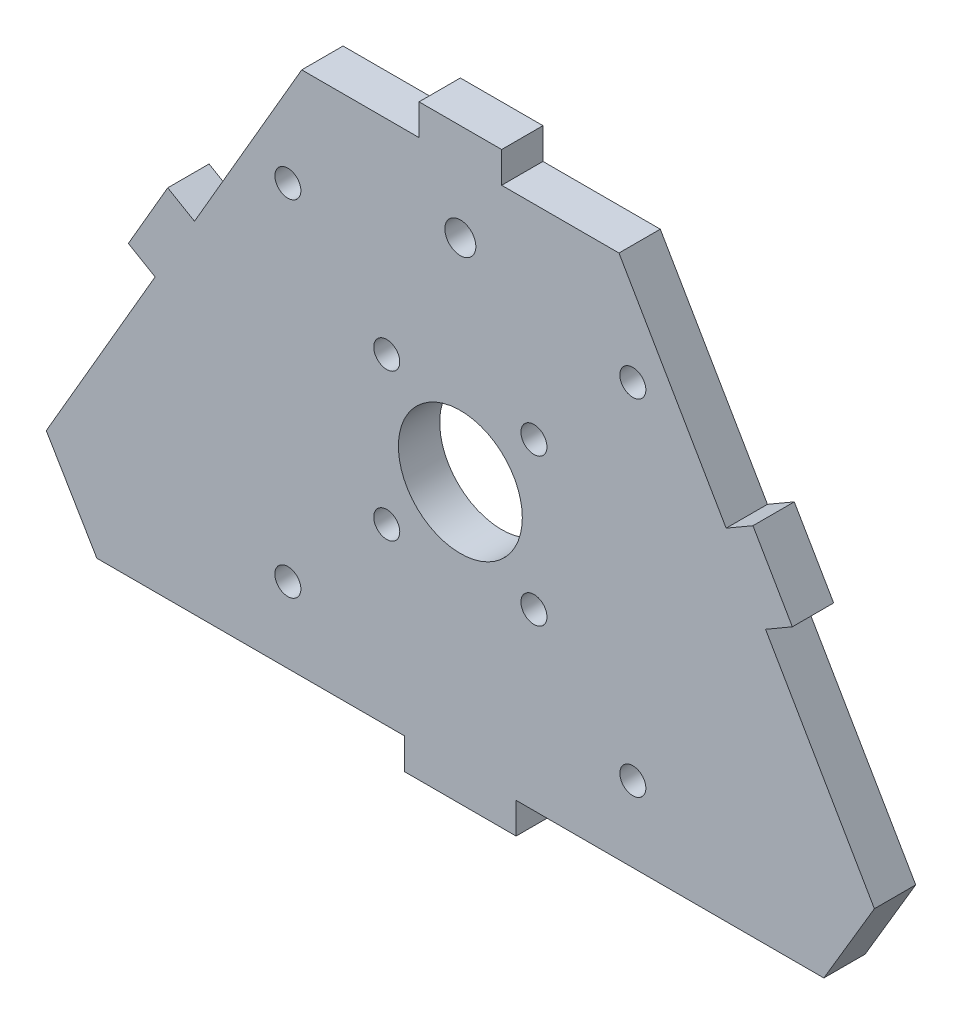
SolidWorks part; units mm, degrees
material "Teak"
ref_plane "Front Plane" through (0, 0, 0) normal (0, 0, 1) x (1, 0, 0)
ref_plane "Top Plane" through (0, 0, 0) normal (0, 1, 0) x (1, 0, 0)
ref_plane "Right Plane" through (0, 0, 0) normal (1, 0, 0) x (0, 0, -1)
sketch "Sketch2" plane through (0, 0, 0) normal (0, 0, 1) x (1, 0, 0)
  line L0 (0, 0) -> (0, -48.7674) construction
  line L1 (0, 0) -> (-45.5415, 0) construction
  line L2 (0, 0) -> (0, 80.772) construction
  line L3 (24.384, 80.772) -> (-24.384, 80.772)
  line L4 (-24.384, 80.772) -> (-63.6522, 13.1092)
  line L7 (-55.88, 0) -> (55.88, 0)
  line L8 (-63.6522, 13.1092) -> (-55.88, 0)
  line L9 (63.6522, 13.1092) -> (55.88, 0)
  line L10 (24.384, 80.772) -> (63.6522, 13.1092)
  dimension "D1" = 80.772
  dimension "D2" = 55.88
  dimension "D3" = 24.384
  dimension "D4" = 15.24
  dimension "D5" = 78.232
extrude "Boss-Extrude1" add sketch "Sketch2" along normal blind 6.35
sketch "Sketch3" plane through (0, 0, 6.35) normal (0, 0, 1) x (1, 0, 0)
  line L0 (0, 80.772) -> (0, 0) construction
  line L2 (0, 38.1) -> (49.1487, 38.1) construction
  line L7 (-11.3137, 49.4137) -> (11.3137, 49.4137) construction
  line L8 (-11.3137, 49.4137) -> (-11.3137, 26.7863) construction
  line L13 (-11.3137, 26.7863) -> (11.3137, 26.7863) construction
  line L14 (11.3137, 49.4137) -> (11.3137, 26.7863) construction
  line L15 (-11.3137, 49.4137) -> (11.3137, 26.7863) construction
  line L16 (-11.3137, 26.7863) -> (11.3137, 49.4137) construction
  line L17 (-26.5165, 64.6165) -> (26.5165, 64.6165) construction
  line L18 (-26.5165, 64.6165) -> (-26.5165, 11.5835) construction
  line L19 (-26.5165, 11.5835) -> (26.5165, 11.5835) construction
  line L20 (26.5165, 64.6165) -> (26.5165, 11.5835) construction
  line L21 (-26.5165, 64.6165) -> (26.5165, 11.5835) construction
  line L22 (-26.5165, 11.5835) -> (26.5165, 64.6165) construction
  line L23 (24.384, 80.772) -> (-24.384, 80.772) construction
  line L24 (-55.88, 0) -> (55.88, 0) construction
  line L25 (63.6522, 13.1092) -> (24.384, 80.772) construction
  circle A10 centre (0, 38.1) radius 9.525
  circle A11 centre (-11.3137, 49.4137) radius 2
  circle A12 centre (-11.3137, 26.7863) radius 2
  circle A13 centre (11.3137, 26.7863) radius 2
  circle A14 centre (11.3137, 49.4137) radius 2
  circle A15 centre (26.5165, 64.6165) radius 2
  circle A16 centre (-26.5165, 64.6165) radius 2
  circle A17 centre (-26.5165, 11.5835) radius 2
  circle A18 centre (26.5165, 11.5835) radius 2
  circle A19 centre (0, 70.612) radius 2.3812
  point P22 (0, 0)
  dimension "D1" = 32
  dimension "D2" = 75
  dimension "D5" = 38.1
  dimension "D7" = 10.16
  dimension "D3" = 19.05
  dimension "D4" = 4
  dimension "D6" = 4.7625
extrude "Cut-Extrude1" cut sketch "Sketch3" against normal blind 6.35
sketch "Sketch4" plane through (0, 0, 0) normal (0, -1, 0) x (1, 0, 0)
  line L0 (0, 6.35) -> (0, 0) construction
  line L1 (-55.88, 6.35) -> (55.88, 6.35) construction
  line L2 (-55.88, 0) -> (55.88, 0) construction
  line L3 (-8.5725, 6.35) -> (8.5725, 6.35)
  line L4 (-8.5725, 6.35) -> (-8.5725, 0)
  line L5 (-8.5725, 0) -> (8.5725, 0)
  line L6 (8.5725, 6.35) -> (8.5725, 0)
  line L7 (-8.5725, 6.35) -> (8.5725, 0) construction
  line L8 (-8.5725, 0) -> (8.5725, 6.35) construction
  point P5 (0, 3.175)
  dimension "D1" = 17.145
extrude "Boss-Extrude2" add sketch "Sketch4" along normal blind 4.7625
sketch "Sketch5" plane through (-53.3062, 30.9363, 0) normal (-0.8649, 0.5019, 0) x (0, 0, 1)
  line L0 (3.175, 57.6202) -> (3.175, -20.6118) construction
  line L1 (6.35, 57.6202) -> (0, 57.6202) construction
  line L2 (6.35, -20.6118) -> (0, -20.6118) construction
  line L3 (6.35, 57.6202) -> (6.35, -20.6118) construction
  line L4 (0, 24.7907) -> (6.35, 24.7907)
  line L5 (0, 24.7907) -> (0, 12.7257)
  line L6 (0, 12.7257) -> (6.35, 12.7257)
  line L7 (6.35, 24.7907) -> (6.35, 12.7257)
  line L8 (0, 24.7907) -> (6.35, 12.7257) construction
  line L9 (0, 12.7257) -> (6.35, 24.7907) construction
  point P6 (3.175, 18.7582)
  dimension "D1" = 39.37
  dimension "D2" = 12.065
extrude "Boss-Extrude3" add sketch "Sketch5" along normal blind 4.7625
sketch "Sketch6" plane through (53.3062, 30.9363, 0) normal (0.8649, 0.5019, 0) x (0, 0, -1)
  line L0 (-3.175, 57.6202) -> (-3.175, -20.6118) construction
  line L1 (-6.35, 57.6202) -> (0, 57.6202) construction
  line L2 (-6.35, -20.6118) -> (0, -20.6118) construction
  line L3 (0, -20.6118) -> (0, 57.6202) construction
  line L4 (-6.35, 24.7907) -> (0, 24.7907)
  line L5 (-6.35, 24.7907) -> (-6.35, 12.7257)
  line L6 (-6.35, 12.7257) -> (0, 12.7257)
  line L7 (0, 24.7907) -> (0, 12.7257)
  line L8 (-6.35, 24.7907) -> (0, 12.7257) construction
  line L9 (-6.35, 12.7257) -> (0, 24.7907) construction
  point P6 (-3.175, 18.7582)
  dimension "D1" = 39.37
  dimension "D2" = 12.065
extrude "Boss-Extrude4" add sketch "Sketch6" along normal blind 4.7625
sketch "Sketch7" plane through (0, 80.772, 0) normal (0, 1, 0) x (1, 0, 0)
  line L0 (0, 0) -> (0, -6.35) construction
  line L1 (24.384, 0) -> (-24.384, 0) construction
  line L2 (24.384, -6.35) -> (-24.384, -6.35) construction
  line L4 (-6.35, 0) -> (6.35, 0)
  line L5 (-6.35, 0) -> (-6.35, -6.35)
  line L6 (-6.35, -6.35) -> (6.35, -6.35)
  line L7 (6.35, 0) -> (6.35, -6.35)
  line L8 (-6.35, 0) -> (6.35, -6.35) construction
  line L9 (-6.35, -6.35) -> (6.35, 0) construction
  point P6 (0, -3.175)
  dimension "D1" = 12.7
extrude "Boss-Extrude5" add sketch "Sketch7" along normal blind 4.7625
